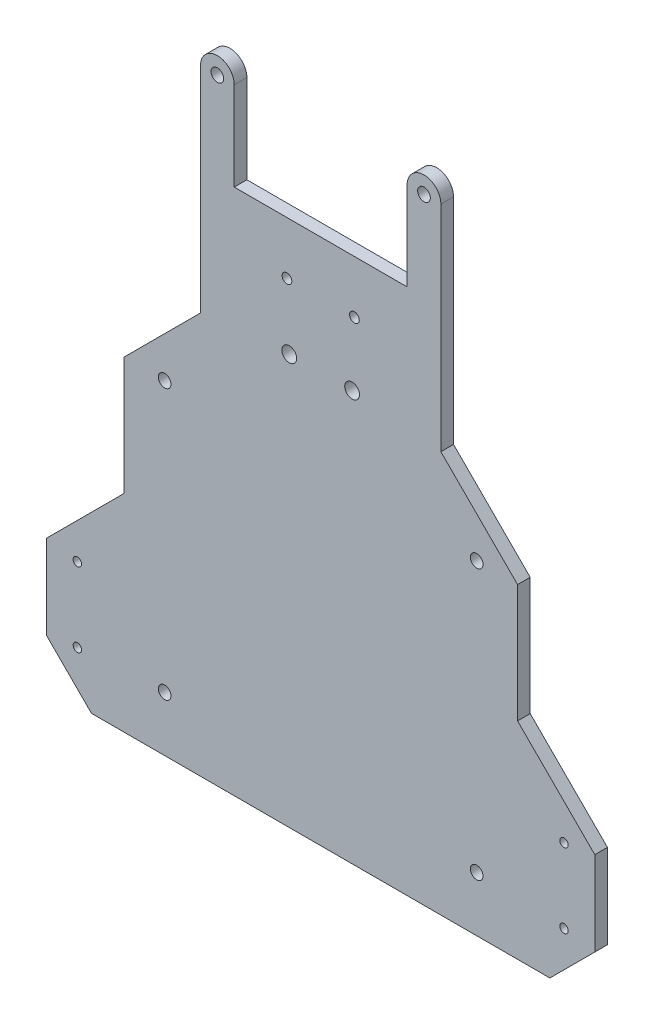
SolidWorks part; units mm, degrees
ref_plane "前视基准面" through (0, 0, 0) normal (0, 0, 1) x (1, 0, 0)
ref_plane "上视基准面" through (0, 0, 0) normal (0, 1, 0) x (1, 0, 0)
ref_plane "右视基准面" through (0, 0, 0) normal (1, 0, 0) x (0, 0, -1)
other "Configuration Table"
sketch "Model" plane through (0, 0, 0) normal (0, 0, 1) x (1, 0, 0)
  line L0 (-46.6892, 48.9634) -> (-65, 30.6526)
  line L1 (-46.6892, 76.9634) -> (-46.6892, 48.9634)
  line L2 (-28.5, 95.1526) -> (-46.6892, 76.9634)
  line L3 (-28.5, 146) -> (-28.5, 95.1526)
  line L4 (-20.5, 125) -> (-20.5, 146)
  line L5 (20.5, 125) -> (-20.5, 125)
  line L6 (20.5, 146) -> (20.5, 125)
  line L7 (28.5, 95.1526) -> (28.5, 146)
  line L8 (46.6892, 76.9634) -> (28.5, 95.1526)
  line L9 (46.6892, 48.9634) -> (46.6892, 76.9634)
  line L10 (65, 30.6526) -> (46.6892, 48.9634)
  line L11 (65, 10.6526) -> (65, 30.6526)
  line L12 (54.3474, 0) -> (65, 10.6526)
  line L13 (-54.3474, 0) -> (54.3474, 0)
  line L14 (-65, 10.6526) -> (-54.3474, 0)
  line L15 (-65, 30.6526) -> (-65, 10.6526)
  line L16 (0, 136.8559) -> (0, -25.8131) construction
  circle A0 centre (7.45, 97.1949) radius 1.75
  circle A1 centre (8, 112.5) radius 1.15
  circle A2 centre (-24.5, 146) radius 1.5
  circle A3 centre (37, 13) radius 1.5
  circle A4 centre (37, 77) radius 1.5
  circle A5 centre (57.7, 11.8526) radius 1
  circle A6 centre (-57.7, 11.8526) radius 1
  circle A7 centre (-57.7, 29.4526) radius 1
  circle A8 centre (57.7, 29.4526) radius 1
  circle A9 centre (-37, 77) radius 1.5
  circle A10 centre (-37, 13) radius 1.5
  circle A11 centre (24.5, 146) radius 1.5
  circle A12 centre (-8, 112.5) radius 1.15
  circle A13 centre (-7.45, 97.1949) radius 1.75
  arc A14 (-20.5, 146) -> (-28.5, 146) centre (-24.5, 146) ccw
  arc A15 (28.5, 146) -> (20.5, 146) centre (24.5, 146) ccw
  dimension "D11" = 2
  dimension "D12" = 3
  dimension "D13" = 2.3
  dimension "D14" = 3.5
  dimension "D15" = 3
  dimension "D20" = 3
  dimension "D1" = 17.6
  dimension "D2" = 7.3
  dimension "D3" = 13
  dimension "D4" = 74
  dimension "D5" = 64
  dimension "D6" = 8
  dimension "D7" = 14.9
  dimension "D8" = 49
  dimension "D9" = 146
  dimension "D10" = 65
  dimension "D16" = 135
  dimension "D17" = 135
  dimension "D18" = 135
  dimension "D19" = 135
extrude "凸台-拉伸1" add sketch "Model" along normal blind 3
